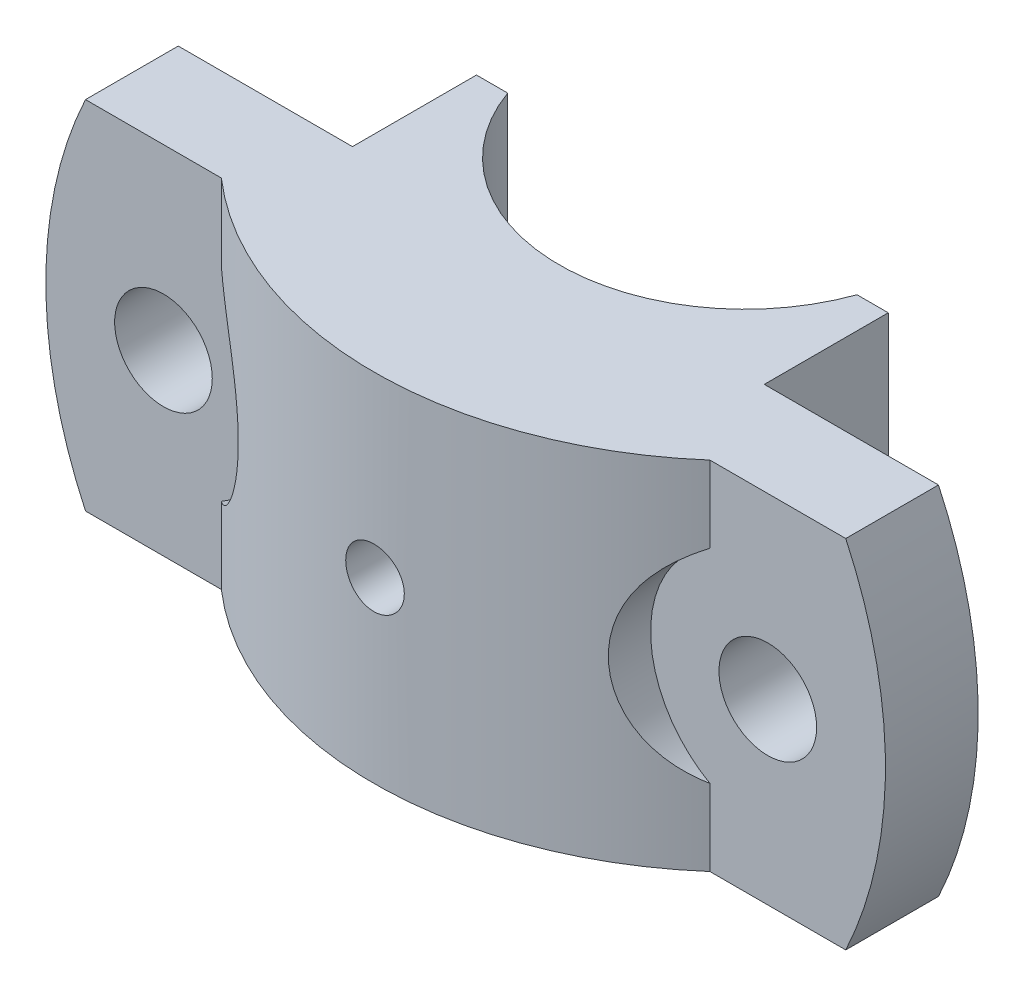
SolidWorks part; units mm, degrees
ref_plane "Front Plane" through (0, 0, 0) normal (0, 0, 1) x (1, 0, 0)
ref_plane "Top Plane" through (0, 0, 0) normal (0, 1, 0) x (1, 0, 0)
ref_plane "Right Plane" through (0, 0, 0) normal (1, 0, 0) x (0, 0, -1)
sketch "Sketch3" plane through (0, 0, 0) normal (0, 0, 1) x (1, 0, 0)
  line L1 (-38.935, 18.25) -> (38.935, 18.25)
  line L3 (-38.935, -18.25) -> (38.935, -18.25)
  line L5 (-38.935, 18.25) -> (38.935, -18.25) construction
  line L6 (-38.935, -18.25) -> (38.935, 18.25) construction
  arc A0 (-38.935, 18.25) -> (-38.935, -18.25) centre (0, 0) ccw
  arc A1 (38.935, -18.25) -> (38.935, 18.25) centre (0, 0) ccw
  dimension "D1" = 86
  dimension "D2" = 36.5
extrude "Boss-Extrude1" add sketch "Sketch3" along normal blind 9.5
sketch "Sketch4" plane through (0, 0, 9.5) normal (0, 0, 1) x (1, 0, 0)
  circle A0 centre (-30.95, 0) radius 5
  circle A1 centre (30.95, 0) radius 5
  dimension "D1" = 10
  dimension "D2" = 10
  dimension "D3" = 30.95
  dimension "D4" = 30.95
extrude "Cut-Extrude1" cut sketch "Sketch4" against normal blind 9.5
sketch "Sketch7" plane through (0, -18.25, 0) normal (0, -1, 0) x (1, 0, 0)
  line L0 (0, 0) -> (0, -0.1)
  line L1 (0, 18.9) -> (0, 9.5)
  line L2 (-38.935, 0) -> (38.935, 0) construction
  line L3 (-38.935, 9.5) -> (38.935, 9.5) construction
  line L4 (-21.0897, 0) -> (0, 0)
  line L5 (-25.0208, 9.5) -> (0, 9.5)
  line L6 (-17.8897, -12.7) -> (-21.0897, -12.7)
  line L7 (-21.0897, -12.7) -> (-21.0897, 0)
  arc A1 (0, -0.1) -> (-17.8897, -12.7) centre (0, -19.1) ccw
  arc A2 (0, 18.9) -> (-25.0208, 9.5) centre (0, -19.1) ccw
  dimension "D4" = 38
  dimension "D1" = 3.2
extrude "Boss-Extrude2" add sketch "Sketch7" against normal blind 36.5
mirror "Mirror1" about plane through (0, 0, 0) normal (1, 0, 0) of "Boss-Extrude2"
sketch "Sketch8" plane through (0, 0, 9.5) normal (0, 0, 1) x (1, 0, 0)
  circle A0 centre (-30.95, 0) radius 12
  dimension "D1" = 24
extrude "Cut-Extrude2" cut sketch "Sketch8" along normal through all
mirror "Mirror2" about plane through (0, 0, 0) normal (1, 0, 0) of "Cut-Extrude2"
sketch "Sketch9" plane through (0, 0, 0) normal (1, 0, 0) x (0, 0, -1)
  line L0 (-18.9, 0) -> (-18.9, 3)
  line L1 (-18.9, 18.25) -> (-18.9, -18.25) construction
  line L2 (-18.9, 3) -> (0, 3)
  line L3 (0, -18.25) -> (0, 18.25) construction
  line L4 (0, 3) -> (0, 2)
  line L5 (0, 2) -> (13.7283, 2)
  line L6 (13.7283, 2) -> (13.7283, 0)
  line L7 (13.7283, 0) -> (-18.9, 0)
  dimension "D1" = 3
  dimension "D2" = 1
revolve "Cut-Revolve1" cut sketch "Sketch9" angle 360 about L7
